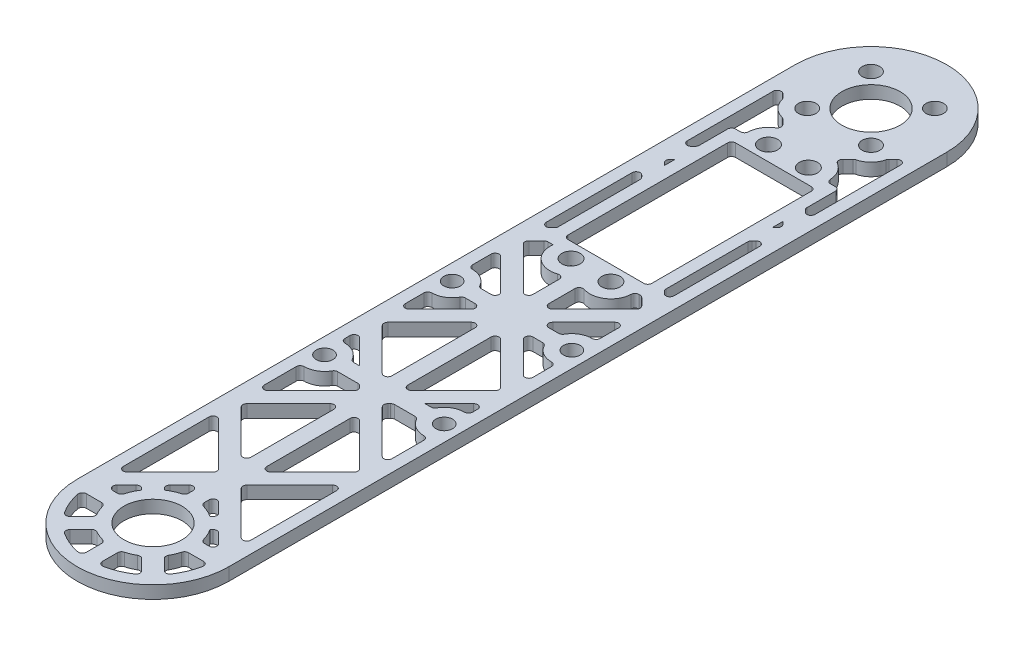
SolidWorks part; units mm, degrees
material "6061-T6 (SS)"
ref_plane "Front Plane" through (0, 0, 0) normal (0, 0, 1) x (1, 0, 0)
ref_plane "Top Plane" through (0, 0, 0) normal (0, 1, 0) x (1, 0, 0)
ref_plane "Right Plane" through (0, 0, 0) normal (1, 0, 0) x (0, 0, -1)
sketch "Sketch1" plane through (0, 0, 0) normal (0, 1, 0) x (1, 0, 0)
  line L0 (0, 0) -> (37733.9999, 0) construction
  line L1 (0, 0) -> (0, 37733.9999) construction
  line L2 (-19, 90) -> (-19, -90)
  line L3 (-8, 82) -> (8, 82) construction
  line L4 (-8, 82) -> (-8, 98) construction
  line L5 (-8, 98) -> (8, 98) construction
  line L6 (8, 82) -> (8, 98) construction
  line L7 (0, 98) -> (0, 82) construction
  line L8 (-8, 90) -> (8, 90) construction
  line L9 (8, -98) -> (-8, -98) construction
  line L10 (8, -98) -> (8, -82) construction
  line L11 (8, -82) -> (-8, -82) construction
  line L12 (-8, -98) -> (-8, -82) construction
  line L13 (0, -82) -> (0, -98) construction
  line L14 (8, -90) -> (-8, -90) construction
  line L15 (19, 90) -> (19, -90)
  line L16 (-19, 0) -> (-19, 50000) construction
  line L17 (19, 0) -> (19, 50000) construction
  line L18 (-15, 0) -> (-15, 50000) construction
  line L19 (23, 0) -> (23, 50000) construction
  line L20 (-23, 0) -> (-23, 50000) construction
  line L21 (15, 0) -> (15, 50000) construction
  line L22 (0, 0) -> (-35355.3391, 35355.3391) construction
  line L23 (10.5, 23.5452) -> (-10.5, 23.5452)
  line L24 (10.5, 23.5452) -> (10.5, 65.5452)
  line L25 (10.5, 65.5452) -> (-10.5, 65.5452)
  line L26 (-10.5, 23.5452) -> (-10.5, 65.5452)
  line L27 (0, 65.5452) -> (0, 23.5452) construction
  line L28 (10.5, 44.5452) -> (-10.5, 44.5452) construction
  line L29 (-5, 69.2952) -> (5, 69.2952) construction
  line L30 (-5, 69.2952) -> (-5, 19.7952) construction
  line L31 (-5, 19.7952) -> (5, 19.7952) construction
  line L32 (5, 69.2952) -> (5, 19.7952) construction
  line L33 (0, 19.7952) -> (0, 69.2952) construction
  line L34 (-5, 44.5452) -> (5, 44.5452) construction
  line L35 (0, 0) -> (35355.3391, 35355.3391) construction
  line L36 (-75.8437, 111.199) -> (35279.4954, -35244.14) construction
  line L37 (-52.9747, 123.6854) -> (35302.3643, -35231.6536) construction
  line L38 (-124.5684, 89.2131) -> (35230.7706, -35266.126) construction
  line L39 (-154.1581, 83.4474) -> (35201.181, -35271.8916) construction
  line L40 (-221.6173, -186.262) -> (35133.7218, 35169.0771) construction
  line L41 (-297.2701, -226.5594) -> (35058.069, 35128.7796) construction
  line L42 (-167.1815, -202.5369) -> (35188.1575, 35152.8022) construction
  line L43 (-211.8822, -282.5928) -> (35143.4569, 35072.7462) construction
  line L44 (-54.389, 122.2712) -> (35300.9501, -35233.0679) construction
  line L45 (-77.2579, 109.7848) -> (35278.0811, -35245.5542) construction
  line L46 (1.4142, 1.4142) -> (-35353.9248, 35356.7533) construction
  line L47 (-125.9826, 87.7989) -> (35229.3564, -35267.5402) construction
  line L48 (-155.5723, 82.0332) -> (35199.7667, -35273.3059) construction
  line L49 (-295.8559, -227.9736) -> (35059.4832, 35127.3654) construction
  line L50 (-220.2031, -187.6762) -> (35135.136, 35167.6629) construction
  line L51 (1.4142, -1.4142) -> (35356.7533, 35353.9248) construction
  line L52 (-165.7673, -203.9511) -> (35189.5717, 35151.388) construction
  line L53 (-210.468, -284.0071) -> (35144.8711, 35071.332) construction
  line L54 (-51.5605, 125.0996) -> (35303.7785, -35230.2394) construction
  line L55 (-74.4295, 112.6133) -> (35280.9096, -35242.7258) construction
  line L56 (-1.4142, -1.4142) -> (-35356.7533, 35353.9248) construction
  line L57 (-123.1542, 90.6273) -> (35232.1848, -35264.7118) construction
  line L58 (-152.7439, 84.8616) -> (35202.5952, -35270.4774) construction
  line L59 (-298.6843, -225.1452) -> (35056.6547, 35130.1939) construction
  line L60 (-223.0315, -184.8477) -> (35132.3075, 35170.4913) construction
  line L61 (-1.4142, 1.4142) -> (35353.9248, 35356.7533) construction
  line L62 (-168.5958, -201.1227) -> (35186.7433, 35154.2164) construction
  line L63 (-213.2964, -281.1786) -> (35142.0427, 35074.1604) construction
  line L64 (2, 0) -> (2, 37733.9999) construction
  line L65 (-2, 0) -> (-2, 37733.9999) construction
  line L66 (0, -2) -> (37733.9999, -2) construction
  line L67 (0, 2) -> (37733.9999, 2) construction
  circle A0 centre (0, 90) radius 7.3
  circle A1 centre (0, -90) radius 7.3
  circle A2 centre (0, 90) radius 16 construction
  circle A3 centre (0, -90) radius 16 construction
  circle A4 centre (-8, 98) radius 2.2
  circle A5 centre (8, 98) radius 2.2
  circle A6 centre (-8, 82) radius 2.2
  circle A7 centre (8, 82) radius 2.2
  circle A8 centre (0, 90) radius 19 construction
  circle A9 centre (0, -90) radius 19 construction
  arc A10 (-19, 90) -> (19, 90) centre (0, 90) cw
  arc A11 (-19, -90) -> (19, -90) centre (0, -90) ccw
  circle A12 centre (-5, 69.2952) radius 2.3
  circle A13 centre (5, 69.2952) radius 2.3
  circle A14 centre (5, 19.7952) radius 2.3
  circle A15 centre (-5, 19.7952) radius 2.3
  circle A24 centre (15, 0) radius 2.1
  circle A25 centre (15, -32) radius 2.1
  circle A26 centre (-15, 0) radius 2.1
  circle A27 centre (-15, -32) radius 2.1
  point P40 (-19, 0)
  point P43 (19, 0)
  point P57 (0, 44.5452)
  point P61 (0, 44.5452)
  dimension "D1" = 14.6
  dimension "D2" = 14.6
  dimension "D5" = 32
  dimension "D7" = 4.4
  dimension "35" = 38
  dimension "D15" = 4.6
  dimension "D8" = 4.2
  dimension "D3" = 90
  dimension "D4" = 90
  dimension "D6" = 16
  dimension "D11" = 42
  dimension "D12" = 21
  dimension "D13" = 10
  dimension "D14" = 49.5
  dimension "D16" = 45
  dimension "D17" = 25
  dimension "D18" = 25
  dimension "D19" = 25
  dimension "D20" = 25
  dimension "D21" = 25
  dimension "D22" = 25
  dimension "D23" = 25
  dimension "D24" = 25
  dimension "D29" = 32
  dimension "D9" = 4
  dimension "D10" = 4
  dimension "D25" = 2
  dimension "D26" = 2
  dimension "D27" = 2
  dimension "D28" = 2
  dimension "D30" = 2
  dimension "D31" = 2
extrude "Boss-Extrude2" add sketch "Sketch1" along normal blind 3.175
sketch "Sketch2" plane through (0, 3.175, 0) normal (0, 1, 0) x (1, 0, 0)
  line L0 (-13.5, 68.5452) -> (-13.5, 20.5452) construction
  line L1 (-13.5, 20.5452) -> (13.5, 20.5452) construction
  line L6 (13.5, 20.5452) -> (13.5, 68.5452) construction
  line L7 (13.5, 68.5452) -> (-13.5, 68.5452) construction
  line L8 (-19, 90) -> (-19, -90)
  line L9 (19, -90) -> (19, 90)
  line L10 (-10.5, 65.5452) -> (-10.5, 23.5452)
  line L11 (10.5, 65.5452) -> (-10.5, 65.5452)
  line L12 (10.5, 23.5452) -> (10.5, 65.5452)
  line L13 (-10.5, 23.5452) -> (10.5, 23.5452)
  line L14 (-10.5, 65.5452) -> (-10.5, 23.5452) construction
  line L15 (10.5, 65.5452) -> (-10.5, 65.5452) construction
  line L16 (10.5, 23.5452) -> (10.5, 65.5452) construction
  line L17 (-10.5, 23.5452) -> (10.5, 23.5452) construction
  line L18 (-19, 90) -> (-19, -90) construction
  line L19 (19, -90) -> (19, 90) construction
  line L20 (-22, 90) -> (-22, -90) construction
  line L21 (22, -90) -> (22, 90) construction
  line L22 (-16, 90) -> (-16, -90) construction
  line L23 (16, -90) -> (16, 90) construction
  line L24 (0, 0) -> (0, 50000) construction
  line L25 (0, 0) -> (50000, 0) construction
  line L26 (0, 0) -> (-34966.926, 34966.926) construction
  line L27 (0, 0) -> (34966.926, 34966.926) construction
  line L28 (-61.3396, 96.695) -> (35293.9994, -35258.6441) construction
  line L29 (-52.5756, 123.2862) -> (35302.7635, -35232.0528) construction
  line L30 (-138.9176, 103.5622) -> (35216.4215, -35251.7768) construction
  line L31 (-203.3188, 132.6081) -> (35152.0202, -35222.7309) construction
  line L32 (114.4084, 149.7637) -> (-35240.9307, -35205.5754) construction
  line L33 (194.9897, 159.6343) -> (-35160.3494, -35195.7047) construction
  line L34 (352.3585, 281.6478) -> (-35002.9806, -35073.6913) construction
  line L35 (191.1578, 261.8684) -> (-35164.1813, -35093.4706) construction
  line L36 (1.4142, 1.4142) -> (-34965.5117, 34968.3402) construction
  line L37 (-62.7538, 95.2807) -> (35292.5852, -35260.0583) construction
  line L38 (-53.9898, 121.872) -> (35301.3493, -35233.467) construction
  line L39 (-140.3318, 102.148) -> (35215.0073, -35253.191) construction
  line L40 (-204.733, 131.1939) -> (35150.606, -35224.1451) construction
  line L41 (1.4142, -1.4142) -> (34968.3402, 34965.5117) construction
  line L42 (112.9942, 151.1779) -> (-35242.3449, -35204.1611) construction
  line L43 (193.5755, 161.0486) -> (-35161.7636, -35194.2905) construction
  line L44 (350.9442, 283.062) -> (-35004.3948, -35072.2771) construction
  line L45 (189.7435, 263.2827) -> (-35165.5955, -35092.0564) construction
  line L46 (-1.4142, -1.4142) -> (-34968.3402, 34965.5117) construction
  line L47 (-59.9254, 98.1092) -> (35295.4137, -35257.2299) construction
  line L48 (-51.1613, 124.7004) -> (35304.1777, -35230.6386) construction
  line L49 (-137.5034, 104.9765) -> (35217.8357, -35250.3626) construction
  line L50 (-201.9046, 134.0224) -> (35153.4344, -35221.3167) construction
  line L51 (-1.4142, 1.4142) -> (34965.5117, 34968.3402) construction
  line L52 (115.8226, 148.3495) -> (-35239.5165, -35206.9896) construction
  line L53 (196.4039, 158.2201) -> (-35158.9352, -35197.1189) construction
  line L54 (353.7727, 280.2336) -> (-35001.5664, -35075.1055) construction
  line L55 (192.572, 260.4542) -> (-35162.7671, -35094.8848) construction
  line L56 (2, 0) -> (2, 50000) construction
  line L57 (-2, 0) -> (-2, 50000) construction
  line L59 (16, 59.9533) -> (16, 81.468)
  line L60 (14.2929, 82.1751) -> (13.3033, 81.1855)
  line L61 (8.8145, 76.6967) -> (7.5267, 75.409)
  line L62 (2, 13.8211) -> (2, 7.2426)
  line L63 (3.7071, 6.5355) -> (14.1421, 16.9706)
  line L64 (14.1421, 18.3848) -> (12.2746, 20.2523)
  line L65 (11.5675, 20.5452) -> (11.295, 20.5452)
  line L68 (16, -10.7574) -> (16, -6.1)
  line L69 (16, 10.7574) -> (16, 6.1)
  line L70 (2, -7.2426) -> (2, -28.1127)
  line L71 (3.7071, -28.8198) -> (14.1421, -18.3848)
  line L72 (14.1421, -16.9706) -> (3.7071, -6.5355)
  line L77 (2, -42.598) -> (2, -63.468)
  line L78 (3.7071, -64.1751) -> (14.1421, -53.7401)
  line L79 (3.7071, -41.8909) -> (14.1421, -52.3259)
  line L80 (16, -59.9533) -> (16, -81.468)
  line L81 (14.2929, -82.1751) -> (3.5355, -71.4178)
  line L82 (3.5355, -70.0036) -> (14.2929, -59.2462)
  line L83 (0, -90) -> (-35355.3391, 35265.3391) construction
  line L84 (0, -90) -> (35355.3391, 35265.3391) construction
  line L85 (1.4142, -91.4142) -> (35356.7533, 35263.9248) construction
  line L86 (1.4142, -88.5858) -> (-35353.9248, 35266.7533) construction
  line L87 (-1.4142, -88.5858) -> (35353.9248, 35266.7533) construction
  line L88 (-1.4142, -91.4142) -> (-35356.7533, 35263.9248) construction
  line L89 (2, -77.9533) -> (2, -79.1055)
  line L90 (3.7071, -77.2462) -> (6.1091, -79.6482)
  line L91 (6.1091, -81.0624) -> (5.7304, -81.4412)
  line L92 (8.9376, -83.8909) -> (8.5588, -84.2696)
  line L93 (10.3518, -83.8909) -> (12.7538, -86.2929)
  line L94 (9.1178, -96.2894) -> (11.8065, -98.9781)
  line L96 (2, -100.8945) -> (2, -104.6969)
  line L97 (6.2894, -99.1178) -> (8.9781, -101.8065)
  line L102 (-2, 13.8211) -> (-2, 7.2426)
  line L103 (-3.7071, 6.5355) -> (-14.1421, 16.9706)
  line L104 (-14.1421, 18.3848) -> (-12.2746, 20.2523)
  line L105 (-11.5675, 20.5452) -> (-10.2467, 20.5452)
  line L110 (-3.7071, -28.8198) -> (-14.1421, -18.3848)
  line L111 (-2, -7.2426) -> (-2, -28.1127)
  line L112 (-14.1421, -16.9706) -> (-3.7071, -6.5355)
  line L117 (-2, -42.598) -> (-2, -63.468)
  line L118 (-3.7071, -64.1751) -> (-14.1421, -53.7401)
  line L119 (-3.7071, -41.8909) -> (-14.1421, -52.3259)
  line L120 (-14.2929, -82.1751) -> (-3.5355, -71.4178)
  line L121 (-16, -59.9533) -> (-16, -81.468)
  line L122 (-3.5355, -70.0036) -> (-14.2929, -59.2462)
  line L123 (-2, -77.9533) -> (-2, -79.1055)
  line L124 (-3.7071, -77.2462) -> (-6.1091, -79.6482)
  line L125 (-6.1091, -81.0624) -> (-5.7304, -81.4412)
  line L126 (-2, -100.8945) -> (-2, -104.6969)
  line L127 (-6.2894, -99.1178) -> (-8.9781, -101.8065)
  line L132 (0, -2) -> (50000, -2) construction
  line L133 (0, 2) -> (50000, 2) construction
  line L134 (7.2426, 2) -> (9.6887, 2)
  line L135 (7.2426, -2) -> (9.6887, -2)
  line L136 (6.5355, -3.7071) -> (14.2929, -11.4645)
  line L137 (14.2929, 11.4645) -> (6.5355, 3.7071)
  line L138 (-7.2426, -2) -> (-9.6887, -2)
  line L139 (-6.5355, -3.7071) -> (-14.2929, -11.4645)
  line L140 (-16, -10.7574) -> (-16, -6.1)
  line L141 (-16, 10.7574) -> (-16, 6.1)
  line L142 (-14.2929, 11.4645) -> (-6.5355, 3.7071)
  line L143 (-7.2426, 2) -> (-9.6887, 2)
  line L144 (13.7929, 46.3198) -> (14.2929, 46.8198)
  line L145 (16, 46.1127) -> (16, 24.598)
  line L146 (14.2929, 23.8909) -> (13.7929, 24.3909)
  line L147 (13.5, 25.098) -> (13.5, 45.6127)
  line L148 (13.5, 54.3823) -> (14.1421, 53.7401)
  line L149 (14.1421, 52.3259) -> (13.5, 51.6838)
  line L150 (13.5, 51.6838) -> (13.5, 54.3823)
  line L151 (11.295, 68.5452) -> (12.5, 68.5452)
  line L152 (13.5, 67.5452) -> (13.5, 60.4533)
  line L153 (13.7929, 59.7462) -> (14.2929, 59.2462)
  line L154 (-14.2929, 23.8909) -> (-13.7929, 24.3909)
  line L155 (-16, 46.1127) -> (-16, 24.598)
  line L156 (-13.7929, 46.3198) -> (-14.2929, 46.8198)
  line L157 (-13.5, 25.098) -> (-13.5, 45.6127)
  line L158 (-14.1421, 52.3259) -> (-13.5, 51.6838)
  line L159 (-13.5, 54.3823) -> (-14.1421, 53.7401)
  line L160 (-13.5, 51.6838) -> (-13.5, 54.3823)
  line L161 (-13.7929, 59.7462) -> (-14.2929, 59.2462)
  line L162 (-13.5, 67.5452) -> (-13.5, 60.4533)
  line L163 (-11.295, 68.5452) -> (-12.5, 68.5452)
  line L164 (-8.8145, 76.6967) -> (-7.5267, 75.409)
  line L165 (-14.2929, 82.1751) -> (-13.3033, 81.1855)
  line L166 (-16, 59.9533) -> (-16, 81.468)
  line L167 (0, -90) -> (50000, -90) construction
  line L168 (0, -92) -> (50000, -92) construction
  line L169 (0, -88) -> (50000, -88) construction
  line L170 (10.8945, -92) -> (14.6969, -92)
  line L171 (10.8945, -88) -> (12.0467, -88)
  line L172 (-10.8945, -92) -> (-14.6969, -92)
  line L173 (-9.1178, -96.2894) -> (-11.8065, -98.9781)
  line L174 (-8.9376, -83.8909) -> (-8.5588, -84.2696)
  line L175 (-10.3518, -83.8909) -> (-12.7538, -86.2929)
  line L176 (-10.8945, -88) -> (-12.0467, -88)
  line L177 (15, -32) -> (-49985, -32) construction
  line L178 (15, -30) -> (-49985, -30) construction
  line L179 (15, -34) -> (-49985, -34) construction
  line L180 (-16, -24.598) -> (-16, -25.9)
  line L181 (-14.2929, -23.8909) -> (-8.1838, -30)
  line L182 (-8.1838, -30) -> (-9.6887, -30)
  line L183 (-9.6887, -34) -> (-4.598, -34)
  line L184 (-3.8909, -34.2929) -> (-3.5355, -34.6482)
  line L185 (-3.5355, -36.0624) -> (-14.2929, -46.8198)
  line L186 (-16, -46.1127) -> (-16, -38.1)
  line L187 (16, -24.598) -> (16, -25.9)
  line L188 (14.2929, -23.8909) -> (8.1838, -30)
  line L189 (8.1838, -30) -> (9.6887, -30)
  line L190 (16, -46.1127) -> (16, -38.1)
  line L191 (3.5355, -36.0624) -> (14.2929, -46.8198)
  line L192 (3.8909, -34.2929) -> (3.5355, -34.6482)
  line L193 (9.6887, -34) -> (4.598, -34)
  circle A0 centre (-15, 0) radius 5.1 construction
  circle A1 centre (-15, -32) radius 5.1 construction
  circle A6 centre (15, 0) radius 5.1 construction
  circle A7 centre (0, 90) radius 7.3
  circle A8 centre (0, 90) radius 7.3 construction
  circle A9 centre (0, -90) radius 7.3
  circle A10 centre (0, -90) radius 7.3 construction
  circle A11 centre (-8, 98) radius 2.2
  circle A12 centre (-8, 98) radius 2.2 construction
  circle A13 centre (8, 98) radius 2.2
  circle A14 centre (8, 98) radius 2.2 construction
  circle A15 centre (-8, 82) radius 2.2
  circle A16 centre (-8, 82) radius 2.2 construction
  circle A17 centre (8, 82) radius 2.2
  circle A18 centre (8, 82) radius 2.2 construction
  circle A19 centre (-5, 69.2952) radius 2.3
  circle A20 centre (-5, 69.2952) radius 2.3 construction
  circle A21 centre (5, 69.2952) radius 2.3
  circle A22 centre (5, 69.2952) radius 2.3 construction
  circle A23 centre (5, 19.7952) radius 2.3
  circle A24 centre (5, 19.7952) radius 2.3 construction
  circle A25 centre (-5, 19.7952) radius 2.3
  circle A26 centre (-5, 19.7952) radius 2.3 construction
  circle A27 centre (15, 0) radius 2.1
  circle A28 centre (15, 0) radius 2.1 construction
  circle A29 centre (15, -32) radius 2.1
  circle A30 centre (15, -32) radius 2.1 construction
  circle A31 centre (-15, 0) radius 2.1
  circle A32 centre (-15, 0) radius 2.1 construction
  circle A33 centre (-15, -32) radius 2.1
  circle A34 centre (-15, -32) radius 2.1 construction
  circle A35 centre (15, -32) radius 5.1 construction
  arc A36 (19, 90) -> (-19, 90) centre (0, 90) ccw
  arc A37 (-19, -90) -> (19, -90) centre (0, -90) ccw
  arc A38 (19, 90) -> (-19, 90) centre (0, 90) ccw construction
  arc A39 (-19, -90) -> (19, -90) centre (0, -90) ccw construction
  circle A40 centre (0, -90) radius 10.3 construction
  circle A41 centre (-5, 19.7952) radius 5.3 construction
  circle A42 centre (5, 19.7952) radius 5.3 construction
  circle A43 centre (-5, 69.2952) radius 5.3 construction
  circle A44 centre (5, 69.2952) radius 5.3 construction
  circle A45 centre (0, 90) radius 10.3 construction
  circle A46 centre (-8, 82) radius 5.2 construction
  circle A47 centre (8, 82) radius 5.2 construction
  circle A48 centre (8, 98) radius 5.2 construction
  circle A49 centre (-8, 98) radius 5.2 construction
  arc A50 (22, 90) -> (-22, 90) centre (0, 90) ccw construction
  arc A51 (-22, -90) -> (22, -90) centre (0, -90) ccw construction
  arc A52 (16, 90) -> (-16, 90) centre (0, 90) ccw construction
  arc A53 (-16, -90) -> (16, -90) centre (0, -90) ccw construction
  arc A54 (-16, 90) -> (16, 90) centre (0, 90) ccw construction
  arc A55 (13.041, 80.7238) -> (9.2762, 76.959) centre (8, 82) cw
  arc A56 (7.7205, 73.8437) -> (10.2958, 69.5055) centre (5, 69.2952) cw
  arc A57 (3.3175, 14.7693) -> (10.2958, 19.5849) centre (5, 19.7952) ccw
  arc A62 (2.7345, -80.0696) -> (5.7304, -81.4412) centre (0, -90) cw
  arc A63 (2.7345, -99.9304) -> (5.0882, -98.9554) centre (0, -90) ccw
  arc A64 (3.2, -105.6767) -> (8.8224, -103.3479) centre (0, -90) ccw
  arc A67 (-3.3175, 14.7693) -> (-10.2467, 20.5452) centre (-5, 19.7952) cw
  arc A70 (-2.7345, -80.0696) -> (-5.7304, -81.4412) centre (0, -90) ccw
  arc A71 (-2.7345, -99.9304) -> (-5.0882, -98.9554) centre (0, -90) cw
  arc A72 (-3.2, -105.6767) -> (-8.8224, -103.3479) centre (0, -90) cw
  arc A75 (15, 5.1) -> (10.5594, 2.5082) centre (15, 0) ccw
  arc A76 (10.5594, -2.5082) -> (15, -5.1) centre (15, 0) ccw
  arc A77 (-10.5594, -2.5082) -> (-15, -5.1) centre (-15, 0) cw
  arc A78 (-15, 5.1) -> (-10.5594, 2.5082) centre (-15, 0) cw
  arc A79 (-7.7205, 73.8437) -> (-10.2958, 69.5055) centre (-5, 69.2952) ccw
  arc A80 (-13.041, 80.7238) -> (-9.2762, 76.959) centre (-8, 82) ccw
  arc A81 (8.5588, -84.2696) -> (9.9304, -87.2655) centre (0, -90) cw
  arc A82 (8.9554, -95.0882) -> (9.9304, -92.7345) centre (0, -90) ccw
  arc A83 (15.6767, -93.2) -> (13.3479, -98.8224) centre (0, -90) cw
  arc A84 (-8.9554, -95.0882) -> (-9.9304, -92.7345) centre (0, -90) cw
  arc A85 (-15.6767, -93.2) -> (-13.3479, -98.8224) centre (0, -90) ccw
  arc A86 (-8.5588, -84.2696) -> (-9.9304, -87.2655) centre (0, -90) ccw
  arc A87 (-15, -26.9) -> (-10.5594, -29.4918) centre (-15, -32) cw
  arc A88 (-15, -37.1) -> (-10.5594, -34.5082) centre (-15, -32) ccw
  arc A89 (15, -26.9) -> (10.5594, -29.4918) centre (15, -32) ccw
  arc A90 (15, -37.1) -> (10.5594, -34.5082) centre (15, -32) cw
  arc A91 (16, -59.9533) -> (14.2929, -59.2462) centre (15, -59.9533) ccw
  arc A92 (3.5355, -71.4178) -> (3.5355, -70.0036) centre (4.2426, -70.7107) cw
  arc A93 (12.7538, -86.2929) -> (12.0467, -88) centre (12.0467, -87) cw
  arc A94 (9.9304, -87.2655) -> (10.8945, -88) centre (10.8945, -87) ccw
  arc A95 (8.9376, -83.8909) -> (10.3518, -83.8909) centre (9.6447, -84.598) cw
  arc A96 (-6.1091, -79.6482) -> (-6.1091, -81.0624) centre (-5.402, -80.3553) ccw
  arc A97 (-2, -79.1055) -> (-2.7345, -80.0696) centre (-3, -79.1055) cw
  arc A98 (-2, -77.9533) -> (-3.7071, -77.2462) centre (-3, -77.9533) ccw
  arc A99 (2, -77.9533) -> (3.7071, -77.2462) centre (3, -77.9533) cw
  arc A100 (2, -79.1055) -> (2.7345, -80.0696) centre (3, -79.1055) ccw
  arc A101 (6.1091, -79.6482) -> (6.1091, -81.0624) centre (5.402, -80.3553) cw
  arc A102 (16, -81.468) -> (14.2929, -82.1751) centre (15, -81.468) cw
  arc A103 (14.6969, -92) -> (15.6767, -93.2) centre (14.6969, -93) cw
  arc A104 (11.8065, -98.9781) -> (13.3479, -98.8224) centre (12.5136, -98.271) ccw
  arc A105 (9.9304, -92.7345) -> (10.8945, -92) centre (10.8945, -93) cw
  arc A106 (9.1178, -96.2894) -> (8.9554, -95.0882) centre (9.8249, -95.5823) cw
  arc A107 (5.0882, -98.9554) -> (6.2894, -99.1178) centre (5.5823, -99.8249) cw
  arc A108 (8.8224, -103.3479) -> (8.9781, -101.8065) centre (8.271, -102.5136) ccw
  arc A109 (3.2, -105.6767) -> (2, -104.6969) centre (3, -104.6969) cw
  arc A110 (2.7345, -99.9304) -> (2, -100.8945) centre (3, -100.8945) ccw
  arc A111 (-2, -104.6969) -> (-3.2, -105.6767) centre (-3, -104.6969) cw
  arc A112 (-8.8224, -103.3479) -> (-8.9781, -101.8065) centre (-8.271, -102.5136) cw
  arc A113 (-2.7345, -99.9304) -> (-2, -100.8945) centre (-3, -100.8945) cw
  arc A114 (-5.0882, -98.9554) -> (-6.2894, -99.1178) centre (-5.5823, -99.8249) ccw
  arc A115 (-11.8065, -98.9781) -> (-13.3479, -98.8224) centre (-12.5136, -98.271) cw
  arc A116 (-8.9554, -95.0882) -> (-9.1178, -96.2894) centre (-9.8249, -95.5823) cw
  arc A117 (-10.8945, -92) -> (-9.9304, -92.7345) centre (-10.8945, -93) cw
  arc A118 (-14.6969, -92) -> (-15.6767, -93.2) centre (-14.6969, -93) ccw
  arc A119 (-9.9304, -87.2655) -> (-10.8945, -88) centre (-10.8945, -87) cw
  arc A120 (-8.9376, -83.8909) -> (-10.3518, -83.8909) centre (-9.6447, -84.598) ccw
  arc A121 (-12.7538, -86.2929) -> (-12.0467, -88) centre (-12.0467, -87) ccw
  arc A122 (-14.2929, -82.1751) -> (-16, -81.468) centre (-15, -81.468) cw
  arc A123 (-3.5355, -71.4178) -> (-3.5355, -70.0036) centre (-4.2426, -70.7107) ccw
  arc A124 (-16, -59.9533) -> (-14.2929, -59.2462) centre (-15, -59.9533) cw
  arc A125 (-14.1421, -53.7401) -> (-14.1421, -52.3259) centre (-13.435, -53.033) cw
  arc A126 (-2, -63.468) -> (-3.7071, -64.1751) centre (-3, -63.468) cw
  arc A127 (2, -63.468) -> (3.7071, -64.1751) centre (3, -63.468) ccw
  arc A128 (14.1421, -53.7401) -> (14.1421, -52.3259) centre (13.435, -53.033) ccw
  arc A129 (2, -42.598) -> (3.7071, -41.8909) centre (3, -42.598) cw
  arc A130 (16, -46.1127) -> (14.2929, -46.8198) centre (15, -46.1127) cw
  arc A131 (-3.5355, -34.6482) -> (-3.5355, -36.0624) centre (-4.2426, -35.3553) cw
  arc A132 (-4.598, -34) -> (-3.8909, -34.2929) centre (-4.598, -35) cw
  arc A133 (-9.6887, -34) -> (-10.5594, -34.5082) centre (-9.6887, -35) ccw
  arc A134 (-16, -38.1) -> (-15, -37.1) centre (-15, -38.1) cw
  arc A135 (-14.2929, -46.8198) -> (-16, -46.1127) centre (-15, -46.1127) cw
  arc A136 (-2, -42.598) -> (-3.7071, -41.8909) centre (-3, -42.598) ccw
  arc A137 (16, -38.1) -> (15, -37.1) centre (15, -38.1) ccw
  arc A138 (9.6887, -34) -> (10.5594, -34.5082) centre (9.6887, -35) cw
  arc A139 (3.8909, -34.2929) -> (4.598, -34) centre (4.598, -35) cw
  arc A140 (3.5355, -36.0624) -> (3.5355, -34.6482) centre (4.2426, -35.3553) cw
  arc A141 (9.6887, -30) -> (10.5594, -29.4918) centre (9.6887, -29) ccw
  arc A142 (16, -25.9) -> (15, -26.9) centre (15, -25.9) cw
  arc A143 (16, -24.598) -> (14.2929, -23.8909) centre (15, -24.598) ccw
  arc A144 (-16, -24.598) -> (-14.2929, -23.8909) centre (-15, -24.598) cw
  arc A145 (-16, -25.9) -> (-15, -26.9) centre (-15, -25.9) ccw
  arc A146 (-9.6887, -30) -> (-10.5594, -29.4918) centre (-9.6887, -29) cw
  arc A147 (2, -7.2426) -> (3.7071, -6.5355) centre (3, -7.2426) cw
  arc A148 (14.1421, -18.3848) -> (14.1421, -16.9706) centre (13.435, -17.6777) ccw
  arc A149 (2, -28.1127) -> (3.7071, -28.8198) centre (3, -28.1127) ccw
  arc A150 (-2, -7.2426) -> (-3.7071, -6.5355) centre (-3, -7.2426) ccw
  arc A151 (-14.1421, -18.3848) -> (-14.1421, -16.9706) centre (-13.435, -17.6777) cw
  arc A152 (-3.7071, -28.8198) -> (-2, -28.1127) centre (-3, -28.1127) ccw
  arc A153 (14.2929, -11.4645) -> (16, -10.7574) centre (15, -10.7574) ccw
  arc A154 (16, -6.1) -> (15, -5.1) centre (15, -6.1) ccw
  arc A155 (9.6887, -2) -> (10.5594, -2.5082) centre (9.6887, -3) cw
  arc A156 (7.2426, -2) -> (6.5355, -3.7071) centre (7.2426, -3) ccw
  arc A157 (-14.2929, -11.4645) -> (-16, -10.7574) centre (-15, -10.7574) cw
  arc A158 (-7.2426, -2) -> (-6.5355, -3.7071) centre (-7.2426, -3) cw
  arc A159 (-9.6887, -2) -> (-10.5594, -2.5082) centre (-9.6887, -3) ccw
  arc A160 (-16, -6.1) -> (-15, -5.1) centre (-15, -6.1) cw
  arc A161 (14.2929, 11.4645) -> (16, 10.7574) centre (15, 10.7574) cw
  arc A162 (16, 6.1) -> (15, 5.1) centre (15, 6.1) cw
  arc A163 (9.6887, 2) -> (10.5594, 2.5082) centre (9.6887, 3) ccw
  arc A164 (7.2426, 2) -> (6.5355, 3.7071) centre (7.2426, 3) cw
  arc A165 (-6.5355, 3.7071) -> (-7.2426, 2) centre (-7.2426, 3) cw
  arc A166 (-9.6887, 2) -> (-10.5594, 2.5082) centre (-9.6887, 3) cw
  arc A167 (-16, 6.1) -> (-15, 5.1) centre (-15, 6.1) ccw
  arc A168 (-16, 10.7574) -> (-14.2929, 11.4645) centre (-15, 10.7574) cw
  arc A169 (-14.1421, 16.9706) -> (-14.1421, 18.3848) centre (-13.435, 17.6777) cw
  arc A170 (-12.2746, 20.2523) -> (-11.5675, 20.5452) centre (-11.5675, 19.5452) cw
  arc A171 (-2, 13.8211) -> (-3.3175, 14.7693) centre (-3, 13.8211) ccw
  arc A172 (-2, 7.2426) -> (-3.7071, 6.5355) centre (-3, 7.2426) cw
  arc A173 (2, 7.2426) -> (3.7071, 6.5355) centre (3, 7.2426) ccw
  arc A174 (2, 13.8211) -> (3.3175, 14.7693) centre (3, 13.8211) cw
  arc A175 (11.295, 20.5452) -> (10.2958, 19.5849) centre (11.295, 19.5452) ccw
  arc A176 (12.2746, 20.2523) -> (11.5675, 20.5452) centre (11.5675, 19.5452) ccw
  arc A177 (14.1421, 16.9706) -> (14.1421, 18.3848) centre (13.435, 17.6777) ccw
  arc A178 (13.7929, 24.3909) -> (13.5, 25.098) centre (14.5, 25.098) cw
  arc A179 (16, 24.598) -> (14.2929, 23.8909) centre (15, 24.598) cw
  arc A180 (14.2929, 46.8198) -> (16, 46.1127) centre (15, 46.1127) cw
  arc A181 (13.7929, 46.3198) -> (13.5, 45.6127) centre (14.5, 45.6127) ccw
  arc A182 (-13.7929, 24.3909) -> (-13.5, 25.098) centre (-14.5, 25.098) ccw
  arc A183 (-14.2929, 23.8909) -> (-16, 24.598) centre (-15, 24.598) cw
  arc A184 (-13.7929, 46.3198) -> (-13.5, 45.6127) centre (-14.5, 45.6127) cw
  arc A185 (-16, 46.1127) -> (-14.2929, 46.8198) centre (-15, 46.1127) cw
  arc A186 (-14.1421, 52.3259) -> (-14.1421, 53.7401) centre (-13.435, 53.033) cw
  arc A187 (14.1421, 53.7401) -> (14.1421, 52.3259) centre (13.435, 53.033) cw
  arc A188 (13.3033, 81.1855) -> (13.041, 80.7238) centre (14.0104, 80.4784) ccw
  arc A189 (8.8145, 76.6967) -> (9.2762, 76.959) centre (9.5216, 75.9896) cw
  arc A190 (7.5267, 75.409) -> (7.7205, 73.8437) centre (8.2338, 74.7019) ccw
  arc A191 (11.295, 68.5452) -> (10.2958, 69.5055) centre (11.295, 69.5452) cw
  arc A192 (12.5, 68.5452) -> (13.5, 67.5452) centre (12.5, 67.5452) cw
  arc A193 (13.5, 60.4533) -> (13.7929, 59.7462) centre (14.5, 60.4533) ccw
  arc A194 (14.2929, 59.2462) -> (16, 59.9533) centre (15, 59.9533) ccw
  arc A195 (-14.2929, 59.2462) -> (-16, 59.9533) centre (-15, 59.9533) cw
  arc A196 (-13.7929, 59.7462) -> (-13.5, 60.4533) centre (-14.5, 60.4533) ccw
  arc A197 (-11.295, 68.5452) -> (-10.2958, 69.5055) centre (-11.295, 69.5452) ccw
  arc A198 (-13.5, 67.5452) -> (-12.5, 68.5452) centre (-12.5, 67.5452) cw
  arc A199 (-13.041, 80.7238) -> (-13.3033, 81.1855) centre (-14.0104, 80.4784) ccw
  arc A200 (-8.8145, 76.6967) -> (-9.2762, 76.959) centre (-9.5216, 75.9896) ccw
  arc A201 (-7.7205, 73.8437) -> (-7.5267, 75.409) centre (-8.2338, 74.7019) ccw
  arc A202 (16, 81.468) -> (14.2929, 82.1751) centre (15, 81.468) ccw
  arc A203 (-14.2929, 82.1751) -> (-16, 81.468) centre (-15, 81.468) ccw
  point P331 (16, -57.5391)
  point P334 (2.8284, -70.7107)
  point P337 (14.4609, -88)
  point P340 (10.104, -88)
  point P343 (9.6447, -83.1838)
  point P346 (-6.8162, -80.3553)
  point P349 (-2, -79.896)
  point P352 (-2, -75.5391)
  point P355 (2, -75.5391)
  point P358 (2, -79.896)
  point P361 (6.8162, -80.3553)
  point P364 (16, -83.8823)
  point P367 (15.8745, -92)
  point P370 (12.6392, -99.8108)
  point P373 (10.104, -92)
  point P376 (8.5588, -95.7304)
  point P379 (5.7304, -98.5588)
  point P382 (9.8108, -102.6392)
  point P385 (2, -105.8745)
  point P388 (2, -100.104)
  point P391 (-2, -105.8745)
  point P394 (-9.8108, -102.6392)
  point P397 (-2, -100.104)
  point P400 (-5.7304, -98.5588)
  point P403 (-12.6392, -99.8108)
  point P406 (-8.5588, -95.7304)
  point P409 (-10.104, -92)
  point P412 (-15.8745, -92)
  point P415 (-10.104, -88)
  point P418 (-9.6447, -83.1838)
  point P421 (-14.4609, -88)
  point P424 (-16, -83.8823)
  point P427 (-2.8284, -70.7107)
  point P430 (-16, -57.5391)
  point P433 (-14.8492, -53.033)
  point P436 (-2, -65.8823)
  point P439 (2, -65.8823)
  point P442 (14.8492, -53.033)
  point P445 (2, -40.1838)
  point P448 (16, -48.5269)
  point P451 (-2.8284, -35.3553)
  point P454 (-4.1838, -34)
  point P457 (-10.3085, -34)
  point P460 (-16, -37.001)
  point P463 (-16, -48.5269)
  point P466 (-2, -40.1838)
  point P469 (16, -37.001)
  point P472 (10.3085, -34)
  point P475 (4.1838, -34)
  point P478 (2.8284, -35.3553)
  point P481 (10.3085, -30)
  point P484 (16, -26.999)
  point P487 (16, -22.1838)
  point P490 (-16, -22.1838)
  point P493 (-16, -26.999)
  point P496 (-10.3085, -30)
  point P499 (2, -4.8284)
  point P502 (14.8492, -17.6777)
  point P505 (2, -30.5269)
  point P508 (-2, -4.8284)
  point P511 (-14.8492, -17.6777)
  point P514 (-2, -30.5269)
  point P517 (16, -13.1716)
  point P520 (16, -5.001)
  point P523 (10.3085, -2)
  point P526 (4.8284, -2)
  point P529 (-16, -13.1716)
  point P532 (-4.8284, -2)
  point P535 (-10.3085, -2)
  point P538 (-16, -5.001)
  point P541 (16, 13.1716)
  point P544 (16, 5.001)
  point P547 (10.3085, 2)
  point P550 (4.8284, 2)
  point P553 (-4.8284, 2)
  point P556 (-10.3085, 2)
  point P559 (-16, 5.001)
  point P562 (-16, 13.1716)
  point P565 (-14.8492, 17.6777)
  point P568 (-11.9817, 20.5452)
  point P571 (-2, 15.426)
  point P574 (-2, 4.8284)
  point P577 (2, 4.8284)
  point P580 (2, 15.426)
  point P583 (10.2467, 20.5452)
  point P586 (11.9817, 20.5452)
  point P589 (14.8492, 17.6777)
  point P592 (13.5, 24.6838)
  point P595 (16, 22.1838)
  point P598 (16, 48.5269)
  point P601 (13.5, 46.0269)
  point P604 (-13.5, 24.6838)
  point P607 (-16, 22.1838)
  point P610 (-13.5, 46.0269)
  point P613 (-16, 48.5269)
  point P616 (-14.8492, 53.033)
  point P619 (14.8492, 53.033)
  point P622 (13.0993, 80.9815)
  point P625 (9.0185, 76.9007)
  point P628 (6.4971, 74.3793)
  point P631 (10.2467, 68.5452)
  point P637 (13.5, 60.0391)
  point P640 (16, 57.5391)
  point P643 (-16, 57.5391)
  point P646 (-13.5, 60.0391)
  point P649 (-10.2467, 68.5452)
  point P655 (-13.0993, 80.9815)
  point P658 (-9.0185, 76.9007)
  point P661 (-6.4971, 74.3793)
  point P664 (16, 83.8823)
  point P667 (-16, 83.8823)
  dimension "D21" = 25
  dimension "D22" = 25
  dimension "D23" = 25
  dimension "D24" = 25
  dimension "D30" = 2
  dimension "D31" = 2
  dimension "D41" = 1
  dimension "D42" = 1
  dimension "D43" = 1
  dimension "D44" = 1
  dimension "D45" = 1
  dimension "D46" = 1
  dimension "D47" = 1
  dimension "D48" = 1
  dimension "D49" = 1
  dimension "D50" = 1
  dimension "D51" = 1
  dimension "D52" = 1
  dimension "D53" = 1
  dimension "D54" = 1
  dimension "D55" = 1
  dimension "D56" = 1
  dimension "D57" = 1
  dimension "D58" = 1
  dimension "D59" = 1
  dimension "D60" = 1
  dimension "D61" = 1
  dimension "D62" = 1
  dimension "D63" = 1
  dimension "D64" = 1
  dimension "D65" = 1
  dimension "D66" = 1
  dimension "D67" = 1
  dimension "D68" = 1
  dimension "D69" = 1
  dimension "D70" = 1
  dimension "D71" = 1
  dimension "D72" = 1
  dimension "D73" = 1
  dimension "D74" = 1
  dimension "D75" = 1
  dimension "D76" = 1
  dimension "D77" = 1
  dimension "D78" = 1
  dimension "D79" = 1
  dimension "D80" = 1
  dimension "D81" = 1
  dimension "D82" = 1
  dimension "D83" = 1
  dimension "D84" = 1
  dimension "D85" = 1
  dimension "D86" = 1
  dimension "D87" = 1
  dimension "D88" = 1
  dimension "D89" = 1
  dimension "D90" = 1
  dimension "D91" = 1
  dimension "D92" = 1
  dimension "D93" = 1
  dimension "D94" = 1
  dimension "D95" = 1
  dimension "D96" = 1
  dimension "D97" = 1
  dimension "D98" = 1
  dimension "D99" = 1
  dimension "D100" = 1
  dimension "D101" = 1
  dimension "D102" = 1
  dimension "D103" = 1
  dimension "D104" = 1
  dimension "D105" = 1
  dimension "D106" = 1
  dimension "D107" = 1
  dimension "D108" = 1
  dimension "D109" = 1
  dimension "D110" = 1
  dimension "D111" = 1
  dimension "D112" = 1
  dimension "D113" = 1
  dimension "D114" = 1
  dimension "D115" = 1
  dimension "D116" = 1
  dimension "D117" = 1
  dimension "D118" = 1
  dimension "D119" = 1
  dimension "D120" = 1
  dimension "D121" = 1
  dimension "D122" = 1
  dimension "D123" = 1
  dimension "D124" = 1
  dimension "D125" = 1
  dimension "D126" = 1
  dimension "D127" = 1
  dimension "D128" = 1
  dimension "D129" = 1
  dimension "D130" = 1
  dimension "D131" = 1
  dimension "D132" = 1
  dimension "D133" = 1
  dimension "D134" = 1
  dimension "D135" = 1
  dimension "D136" = 1
  dimension "D137" = 1
  dimension "D138" = 1
  dimension "D139" = 1
  dimension "D140" = 1
  dimension "D141" = 1
  dimension "D142" = 1
  dimension "D143" = 1
  dimension "D144" = 1
  dimension "D145" = 1
  dimension "D146" = 1
  dimension "D147" = 1
  dimension "D148" = 1
  dimension "D149" = 1
  dimension "D150" = 1
  dimension "D151" = 1
  dimension "D152" = 1
  dimension "D153" = 1
  dimension "D20" = 45
  dimension "D25" = 25
  dimension "D26" = 25
  dimension "D27" = 25
  dimension "D28" = 25
  dimension "D1" = 0
  dimension "D2" = 0
  dimension "D3" = 0
  dimension "D4" = 0
  dimension "D5" = 0
  dimension "D6" = 0
  dimension "D11" = 0
  dimension "D12" = 0
  dimension "D13" = 0
  dimension "D14" = 0
  dimension "D16" = 0
  dimension "D17" = 3
  dimension "D18" = 3
  dimension "D19" = 3
  dimension "D29" = 2
  dimension "D32" = 2
  dimension "D33" = 2
  dimension "D34" = 2
  dimension "D35" = 2
  dimension "D36" = 2
  dimension "D37" = 2
  dimension "D38" = 2
  dimension "D39" = 2
  dimension "D40" = 2
extrude "Cut-Extrude1" cut sketch "Sketch2" against normal blind 3.175
fillet "Fillet1" radius 1 4 edges at (-10.5, 1.5875, -23.5452) (10.5, 1.5875, -23.5452) (10.5, 1.5875, -65.5452) (-10.5, 1.5875, -65.5452)
equation "\"pocketing\"= \"strut pocketing\" * 2"
equation "\"strut pocketing\"= 2mm"
equation "\"D10@Sketch1\"=\"pocketing\""
equation "\"D9@Sketch1\"=\"pocketing\""
equation "\"dist struts\"= 25mm"
equation "\"D17@Sketch1\"=\"dist struts\""
equation "\"D18@Sketch1\"=\"dist struts\""
equation "\"D20@Sketch1\"=\"dist struts\""
equation "\"D19@Sketch1\"=\"dist struts\""
equation "\"D21@Sketch1\"=\"dist struts\""
equation "\"D22@Sketch1\"=\"dist struts\""
equation "\"D23@Sketch1\"=\"dist struts\""
equation "\"D24@Sketch1\"=\"dist struts\""
equation "\"D25@Sketch1\"=\"strut pocketing\""
equation "\"D26@Sketch1\"=\"strut pocketing\""
equation "\"D28@Sketch1\"=\"strut pocketing\""
equation "\"D27@Sketch1\"=\"strut pocketing\""
equation "\"D21@Sketch2\"=\"dist struts\""
equation "\"D22@Sketch2\"=\"dist struts\""
equation "\"D23@Sketch2\"=\"dist struts\""
equation "\"D24@Sketch2\"=\"dist struts\""
equation "\"D25@Sketch2\"=\"dist struts\""
equation "\"D26@Sketch2\"=\"dist struts\""
equation "\"D27@Sketch2\"=\"dist struts\""
equation "\"D28@Sketch2\"=\"dist struts\""
equation "\"D31@Sketch2\"=\"strut pocketing\""
equation "\"D32@Sketch2\"=\"strut pocketing\""
equation "\"D29@Sketch2\"=\"strut pocketing\""
equation "\"D30@Sketch2\"=\"strut pocketing\""
equation "\"D34@Sketch2\"=\"strut pocketing\""
equation "\"D33@Sketch2\"=\"strut pocketing\""
equation "\"D31@Sketch1\"=\"strut pocketing\""
equation "\"D30@Sketch1\"=\"strut pocketing\""
equation "\"D36@Sketch2\"=\"strut pocketing\""
equation "\"D35@Sketch2\"=\"strut pocketing\""
equation "\"D38@Sketch2\"=\"strut pocketing\""
equation "\"D37@Sketch2\"=\"strut pocketing\""
equation "\"D39@Sketch2\"=\"strut pocketing\""
equation "\"D40@Sketch2\"=\"strut pocketing\""
